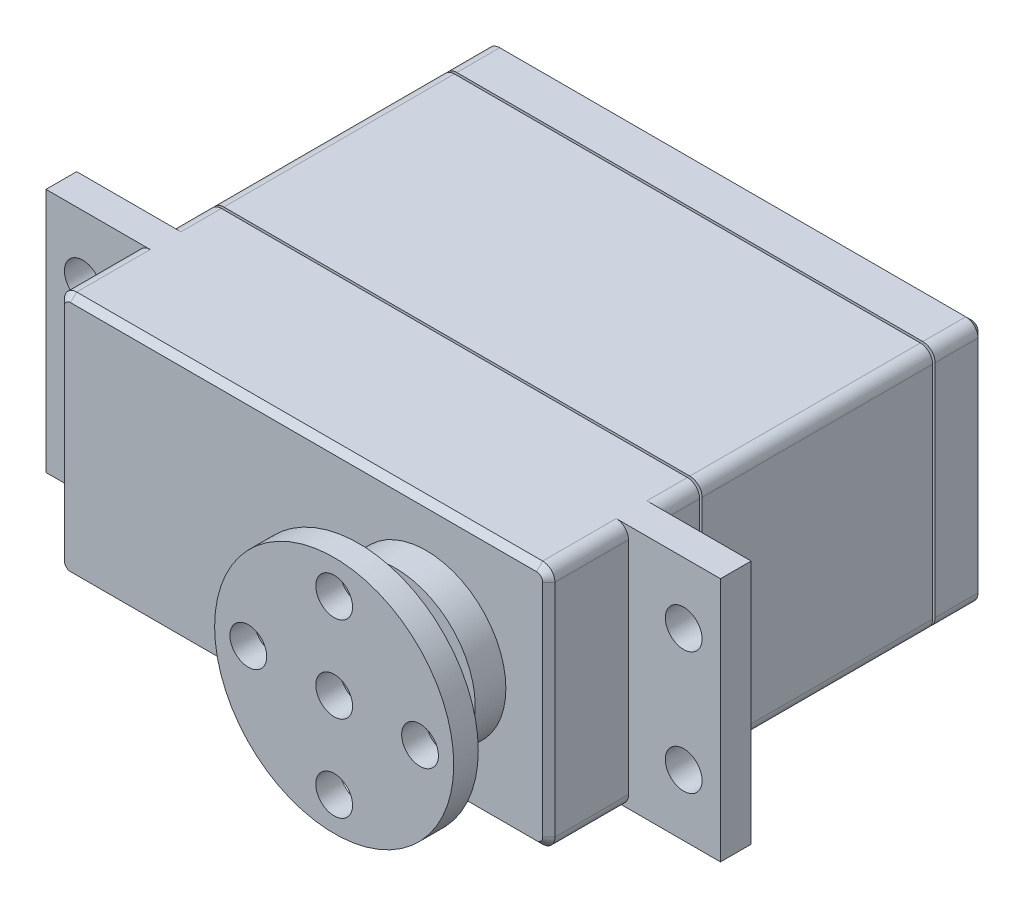
SolidWorks part; units mm, degrees
ref_plane "Front" through (0, 0, 0) normal (0, 0, 1) x (1, 0, 0)
ref_plane "Top" through (0, 0, 0) normal (0, 1, 0) x (1, 0, 0)
ref_plane "Right" through (0, 0, 0) normal (1, 0, 0) x (0, 0, -1)
sketch "草图1" plane through (0, 0, 0) normal (0, 0, 1) x (1, 0, 0)
  line L1 (20, -10) -> (-20, -10)
  line L2 (20, -10) -> (20, 10)
  line L3 (20, 10) -> (-20, 10)
  line L4 (-20, -10) -> (-20, 10)
  line L5 (20, -10) -> (-20, 10) construction
  line L6 (20, 10) -> (-20, -10) construction
  point P0 (0, 0)
  dimension "D1" = 20
  dimension "D2" = 40
extrude "凸台-拉伸1" add sketch "草图1" along normal blind 35.5
sketch "草图2" plane through (0, 0, 35.5) normal (0, 0, 1) x (1, 0, 0)
  line L0 (20, 0) -> (10, 0) construction
  line L1 (20, -10) -> (20, 10) construction
  circle A0 centre (10, 0) radius 6.5
  dimension "D2" = 13
  dimension "D1" = 10
extrude "凸台-拉伸2" add sketch "草图2" along normal blind 2.5
sketch "草图3" plane through (0, 0, 38) normal (0, 0, 1) x (1, 0, 0)
  circle A0 centre (10, 0) radius 4
  dimension "D1" = 8
extrude "凸台-拉伸3" add sketch "草图3" along normal blind 3
sketch "草图4" plane through (0, 0, 41) normal (0, 0, 1) x (1, 0, 0)
  circle A0 centre (10, 0) radius 9.75
  circle A1 centre (10, 0) radius 1.5
  circle A2 centre (10, 0) radius 7 construction
  circle A3 centre (10, 7) radius 1.5
  circle A4 centre (17, 0) radius 1.5
  circle A5 centre (10, -7) radius 1.5
  circle A6 centre (3, 0) radius 1.5
  point P16 (10, 0)
  dimension "D1" = 19.5
  dimension "D2" = 3
  dimension "D3" = 14
  dimension "D4" = 4
extrude "凸台-拉伸4" add sketch "草图4" along normal blind 2
ref_plane "基准面1" through (0, 0, 29) normal (0, 0, 1) x (1, 0, 0)
sketch "草图5" plane through (0, 0, 29) normal (0, 0, 1) x (1, 0, 0)
  line L0 (-20, 10) -> (-27.5, 10)
  line L1 (-27.5, 10) -> (-27.5, -10)
  line L2 (-27.5, -10) -> (-20, -10)
  line L3 (-20, -10) -> (-20, 10)
  line L4 (0, 10) -> (0, 3.6431) construction
  line L5 (20, 10) -> (-20, 10) construction
  line L6 (20, -10) -> (20, 10)
  line L7 (27.5, -10) -> (20, -10)
  line L8 (27.5, 10) -> (27.5, -10)
  line L9 (20, 10) -> (27.5, 10)
  line L10 (-24.5, 10) -> (-24.5, -10) construction
  circle A0 centre (-24.5, 5) radius 1.5
  circle A1 centre (-24.5, -5) radius 1.5
  circle A2 centre (24.5, -5) radius 1.5
  circle A3 centre (24.5, 5) radius 1.5
  point P25 (-24.5, 0)
  dimension "D2" = 3
  dimension "D1" = 55
  dimension "D3" = 49
  dimension "D4" = 10
  dimension "D5" = 5
extrude "凸台-拉伸5" add sketch "草图5" against normal blind 2.5
fillet "圆角1" radius 1 8 edges at (20, 10, 13.25) (20, 10, 32.25) (20, -10, 13.25) (20, -10, 32.25) (-20, 10, 13.25) (-20, 10, 32.25) (-20, -10, 13.25) (-20, -10, 32.25)
chamfer "倒角1" distance 0.5 angle 45 16 edges at (0, -10, 0) (19.7071, -9.7071, 0) (-19.7071, -9.7071, 0) (20, 0, 0) (-20, 0, 0) (19.7071, 9.7071, 0) (-19.7071, 9.7071, 0) (0, 10, 0) (-20, 0, 35.5) (-19.7071, -9.7071, 35.5) (-19.7071, 9.7071, 35.5) (0, -10, 35.5) (0, 10, 35.5) (19.7071, -9.7071, 35.5) (19.7071, 9.7071, 35.5) (20, 0, 35.5)
ref_plane "基准面2" through (0, 0, 23) normal (0, 0, -1) x (-1, 0, 0)
ref_plane "基准面3" through (0, 0, 4) normal (0, 0, -1) x (-1, 0, 0)
sketch "草图6" plane through (0, 0, 4) normal (0, 0, -1) x (-1, 0, 0)
  line L0 (19, -10) -> (-19, -10) construction
  line L1 (-19.5, 9.5) -> (19.5, 9.5)
  line L2 (-19.5, 9.5) -> (-19.5, -9.5)
  line L3 (-19.5, -9.5) -> (19.5, -9.5)
  line L4 (19.5, 9.5) -> (19.5, -9.5)
  line L5 (-19.5, 9.5) -> (19.5, -9.5) construction
  line L6 (-19.5, -9.5) -> (19.5, 9.5) construction
  line L7 (20, -9) -> (20, 9) construction
  line L9 (-25.2613, 12.5798) -> (25.2613, 12.5798)
  line L10 (-25.2613, 12.5798) -> (-25.2613, -12.5798)
  line L11 (-25.2613, -12.5798) -> (25.2613, -12.5798)
  line L12 (25.2613, 12.5798) -> (25.2613, -12.5798)
  line L13 (-25.2613, 12.5798) -> (25.2613, -12.5798) construction
  line L14 (-25.2613, -12.5798) -> (25.2613, 12.5798) construction
  point P0 (0, 0)
  point P10 (0, 0)
  dimension "D1" = 0.5
  dimension "D2" = 0.5
extrude "切除-拉伸1" cut sketch "草图6" against normal blind 0.2
sketch "草图7" plane through (0, 0, 23) normal (0, 0, -1) x (-1, 0, 0)
  line L0 (19, -10) -> (-19, -10) construction
  line L1 (-19.5, 9.5) -> (19.5, 9.5)
  line L2 (-19.5, 9.5) -> (-19.5, -9.5)
  line L3 (-19.5, -9.5) -> (19.5, -9.5)
  line L4 (19.5, 9.5) -> (19.5, -9.5)
  line L5 (-19.5, 9.5) -> (19.5, -9.5) construction
  line L6 (-19.5, -9.5) -> (19.5, 9.5) construction
  line L7 (-22.7382, 12.6011) -> (22.7382, 12.6011)
  line L8 (-22.7382, 12.6011) -> (-22.7382, -12.6011)
  line L9 (-22.7382, -12.6011) -> (22.7382, -12.6011)
  line L10 (22.7382, 12.6011) -> (22.7382, -12.6011)
  line L11 (-22.7382, 12.6011) -> (22.7382, -12.6011) construction
  line L12 (-22.7382, -12.6011) -> (22.7382, 12.6011) construction
  line L13 (20, -9) -> (20, 9) construction
  point P0 (0, 0)
  point P6 (0, 0)
  dimension "D1" = 0.5
  dimension "D2" = 0.5
extrude "切除-拉伸2" cut sketch "草图7" against normal blind 0.2
sketch "草图8" plane through (0, -10, 0) normal (0, -1, 0) x (1, 0, 0)
  text T0 "KST" font "Century Gothic" height in points 22
extrude "切除-拉伸3" cut sketch "草图8" against normal blind 0.2
